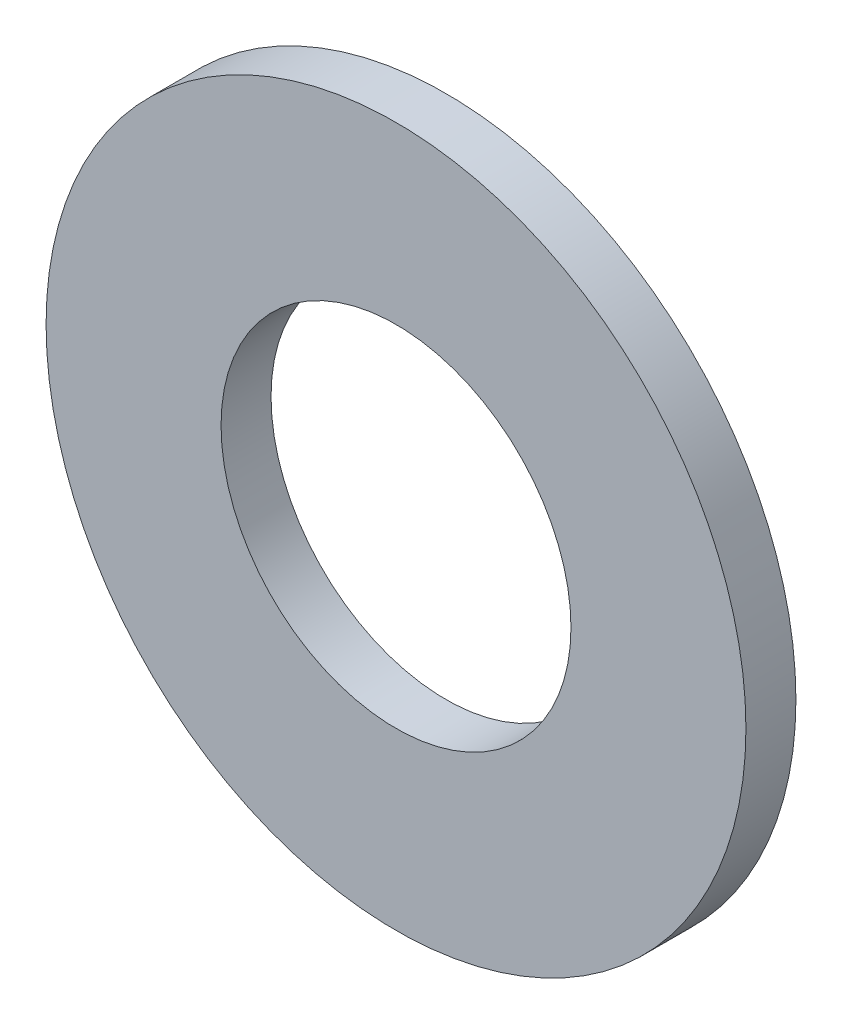
SolidWorks part; units mm, degrees
ref_plane "前视基准面" through (0, 0, 0) normal (0, 0, 1) x (1, 0, 0)
ref_plane "上视基准面" through (0, 0, 0) normal (0, 1, 0) x (1, 0, 0)
ref_plane "右视基准面" through (0, 0, 0) normal (1, 0, 0) x (0, 0, -1)
sketch "草图1" plane through (0, 0, 0) normal (0, 0, 1) x (1, 0, 0)
  circle A0 centre (0, 0) radius 1.75
  circle A1 centre (0, 0) radius 3.5
extrude "凸台-拉伸1" add sketch "草图1" along normal blind 0.5
sketch "草图2" plane through (0, 0, 0.5) normal (0, 0, 1) x (1, 0, 0)
  circle A0 centre (0, 0) radius 1.5
sketch "草图3" plane through (0, 0, 0) normal (0, 0, -1) x (-1, 0, 0)
  circle A0 centre (0, 0) radius 1.5
